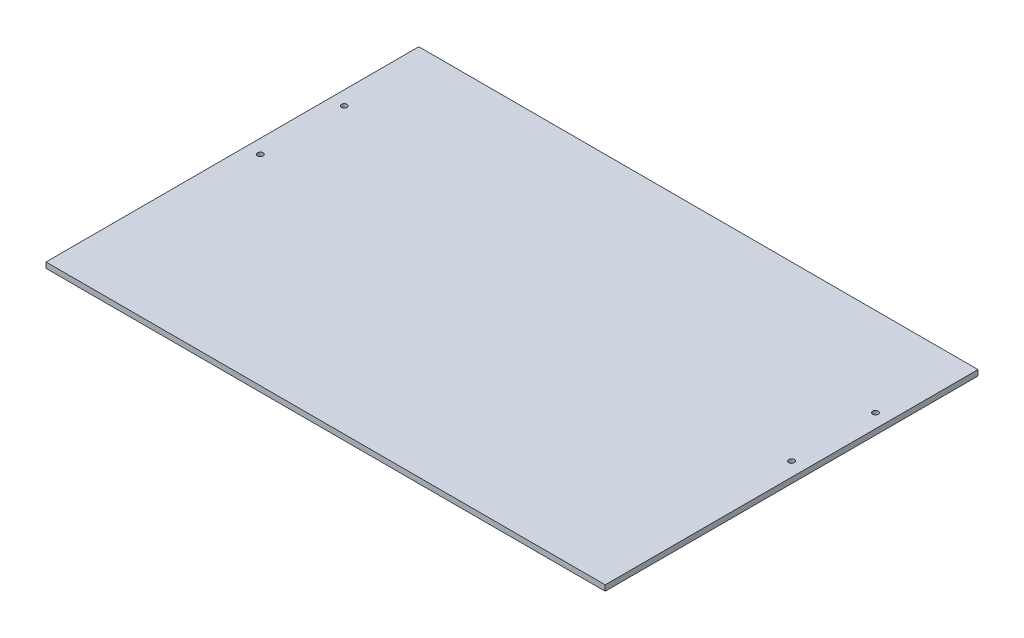
SolidWorks part; units mm, degrees
material "Balsa"
ref_plane "Plano frontal" through (0, 0, 0) normal (0, 0, 1) x (1, 0, 0)
ref_plane "Plano superior" through (0, 0, 0) normal (0, 1, 0) x (1, 0, 0)
ref_plane "Plano direito" through (0, 0, 0) normal (1, 0, 0) x (0, 0, -1)
sketch "Esboço1" plane through (0, 0, 0) normal (0, 1, 0) x (1, 0, 0)
  line L0 (-142.5, 7.5) -> (-142.5, 52.5) construction
  line L1 (-150, -100) -> (150, -100)
  line L2 (-150, -100) -> (-150, 100)
  line L3 (-150, 100) -> (150, 100)
  line L4 (150, -100) -> (150, 100)
  line L5 (-150, -100) -> (150, 100) construction
  line L6 (-150, 100) -> (150, -100) construction
  line L7 (0, 100) -> (0, -100) construction
  line L8 (142.5, 7.5) -> (142.5, 52.5) construction
  circle A0 centre (-142.5, 52.5) radius 1.5
  circle A1 centre (-142.5, 7.5) radius 1.5
  circle A2 centre (142.5, 7.5) radius 1.5
  circle A3 centre (142.5, 52.5) radius 1.5
  point P0 (0, 0)
  point P20 (-142.5, 30)
  dimension "D4" = 3
  dimension "D1" = 200
  dimension "D2" = 300
  dimension "D3" = 45
  dimension "D5" = 7.5
  dimension "D6" = 70
extrude "Ressalto-extrusão1" add sketch "Esboço1" along normal blind 3
